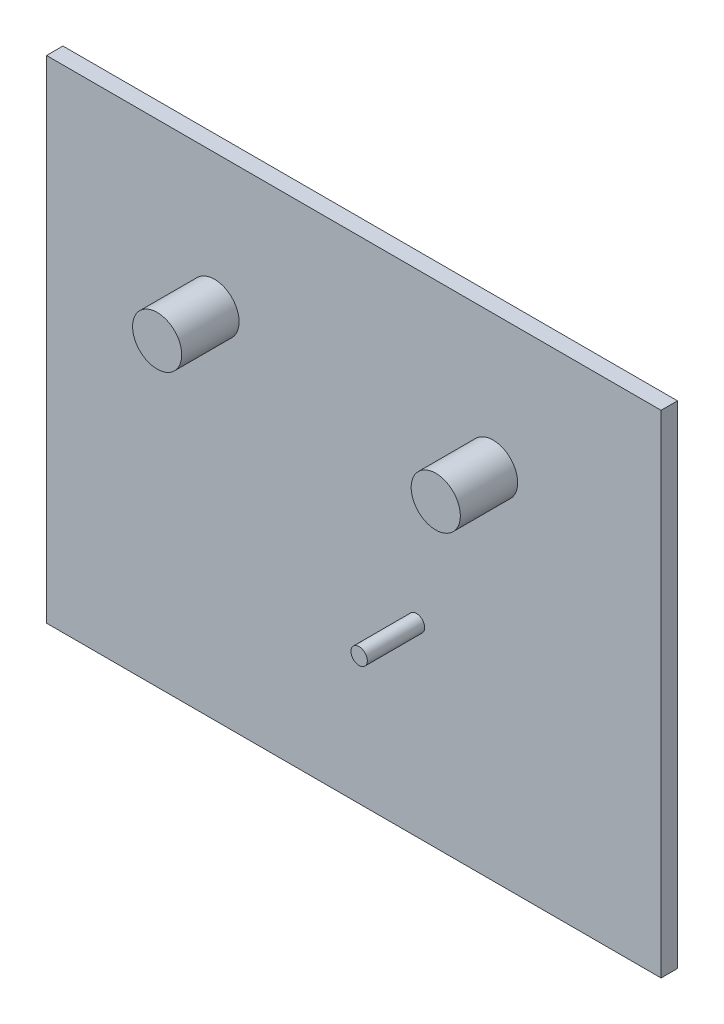
SolidWorks part; units mm, degrees
ref_plane "Plan de face" through (0, 0, 0) normal (0, 0, 1) x (1, 0, 0)
ref_plane "Plan de dessus" through (0, 0, 0) normal (0, 1, 0) x (1, 0, 0)
ref_plane "Plan de droite" through (0, 0, 0) normal (1, 0, 0) x (0, 0, -1)
sketch "Esquisse3" plane through (0, 0, 0) normal (0, 0, 1) x (1, 0, 0)
  line L0 (-17, 13.6) -> (17, 13.6) construction
  line L1 (-37.5, -30) -> (37.5, -30)
  line L2 (-37.5, -30) -> (-37.5, 30)
  line L3 (-37.5, 30) -> (37.5, 30)
  line L4 (37.5, -30) -> (37.5, 30)
  line L5 (-37.5, -30) -> (37.5, 30) construction
  line L6 (-37.5, 30) -> (37.5, -30) construction
  line L7 (17, 13.6) -> (6.0484, -7.4) construction
  circle A0 centre (-17, 13.6) radius 6
  circle A1 centre (17, 13.6) radius 6
  circle A2 centre (6.0484, -7.4) radius 2
  point P0 (0, 0)
  dimension "D4" = 12
  dimension "D5" = 12
  dimension "D6" = 4
  dimension "D1" = 75
  dimension "D2" = 60
  dimension "D3" = 34
  dimension "D7" = 21
extrude "Boss.-Extru.4" add sketch "Esquisse3" along normal blind 2 contours L2 L3 L4 L1
sketch "Esquisse7" plane through (0, 0, 2) normal (0, 0, 1) x (1, 0, 0)
  line L0 (-17, 13.6) -> (17, 13.6) construction
  line L1 (-37.5, 30) -> (37.5, 30) construction
  line L2 (37.5, -30) -> (37.5, 30) construction
  line L5 (-37.5, -30) -> (37.5, 30) construction
  line L6 (-37.5, 30) -> (37.5, -30) construction
  line L7 (17, 13.6) -> (7.6492, -7.4) construction
  circle A0 centre (-17, 13.6) radius 3
  circle A1 centre (17, 13.6) radius 3
  circle A2 centre (7.6492, -7.4) radius 1
  point P0 (0, 0)
  dimension "D4" = 6
  dimension "D5" = 6
  dimension "D6" = 2
  dimension "D1" = 75
  dimension "D2" = 60
  dimension "D3" = 34
  dimension "D7" = 21
extrude "Boss.-Extru.5" add sketch "Esquisse7" along normal blind 7
